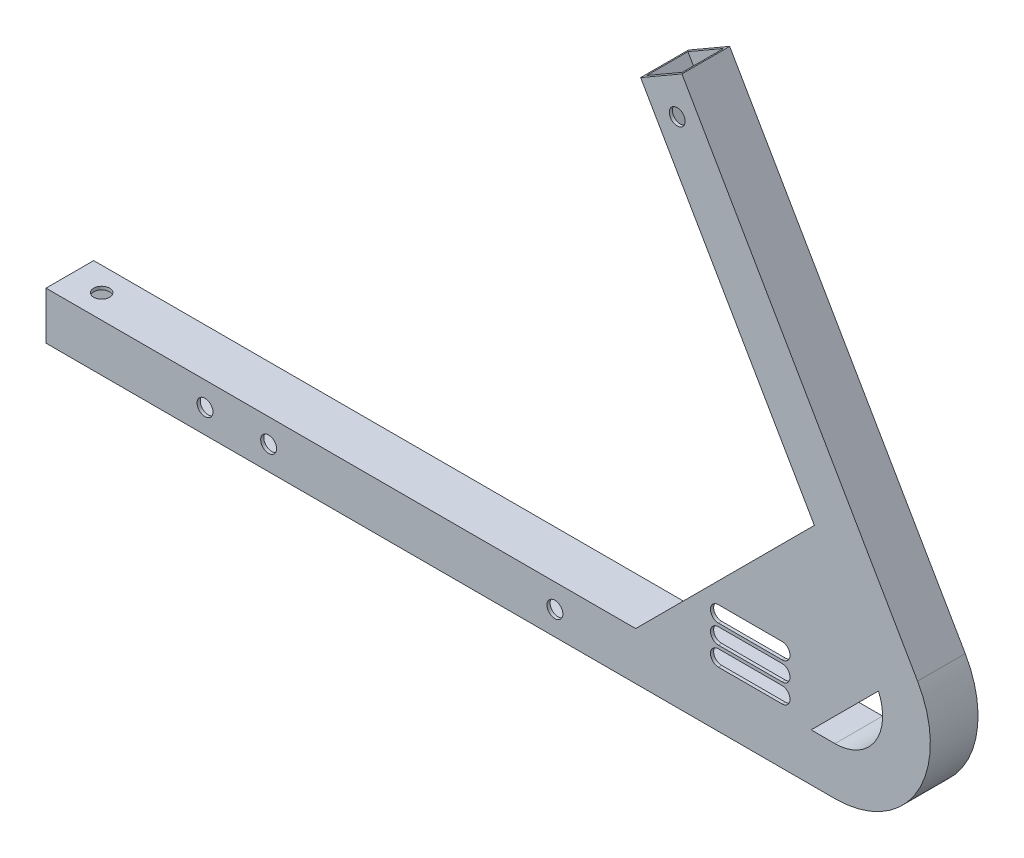
SolidWorks part; units mm, degrees
material "Plain Carbon Steel"
ref_plane "Front Plane" through (0, 0, 0) normal (0, 0, 1) x (1, 0, 0)
ref_plane "Top Plane" through (0, 0, 0) normal (0, 1, 0) x (1, 0, 0)
ref_plane "Right Plane" through (0, 0, 0) normal (1, 0, 0) x (0, 0, -1)
sketch "Sketch1" plane through (0, 0, 0) normal (0, 0, 1) x (1, 0, 0)
  line L0 (102.6529, 330.2) -> (227.3028, 114.3)
  line L1 (161.3117, 0) -> (-468.7061, 0)
  line L2 (69.6573, 311.15) -> (194.3072, 95.25)
  line L3 (161.3117, 38.1) -> (-468.7061, 38.1)
  line L4 (69.6573, 311.15) -> (102.6529, 330.2)
  line L5 (-468.7061, 38.1) -> (-468.7061, 0)
  arc A0 (227.3028, 114.3) -> (161.3117, 0) centre (161.3117, 76.2) cw
  arc A1 (194.3072, 95.25) -> (161.3117, 38.1) centre (161.3117, 76.2) cw
  point P6 (293.2939, 0)
  dimension "D5" = 76.2
  dimension "D1" = 762
  dimension "D2" = 330.2
  dimension "D3" = 60
  dimension "D4" = 254
  dimension "D6" = 38.1
extrude "Boss-Extrude1" add sketch "Sketch1" against normal blind 38.1
shell "Shell1" thickness 2.54
sketch "Sketch3" plane through (-468.7061, 0, 0) normal (-1, 0, 0) x (0, 0, 1)
  line L0 (0, 38.1) -> (0, 0) construction
  line L1 (-35.56, 2.54) -> (-2.54, 2.54)
  line L2 (-35.56, 2.54) -> (-35.56, 35.56)
  line L3 (-35.56, 35.56) -> (-2.54, 35.56)
  line L4 (-2.54, 2.54) -> (-2.54, 35.56)
  line L5 (-35.56, 2.54) -> (-2.54, 35.56) construction
  line L6 (-35.56, 35.56) -> (-2.54, 2.54) construction
  line L7 (-38.1, 38.1) -> (-38.1, 0) construction
  line L8 (-38.1, 0) -> (0, 0) construction
  line L9 (-38.1, 38.1) -> (0, 38.1) construction
  point P0 (-19.05, 19.05)
  dimension "D1" = 2.54
  dimension "D2" = 2.54
  dimension "D3" = 2.54
  dimension "D4" = 2.54
extrude "Cut-Extrude1" cut sketch "Sketch3" against normal up to next
sketch "Sketch4" plane through (0, 0, 0) normal (0, 0, 1) x (1, 0, 0)
  line L0 (2.179, 38.1) -> (144.9018, 180.8228)
  line L1 (161.3117, 38.1) -> (-468.7061, 38.1) construction
  line L2 (69.6573, 311.15) -> (194.3072, 95.25) construction
  line L3 (144.9018, 180.8228) -> (196.1943, 91.9815)
  line L7 (2.179, 38.1) -> (142.3127, 38.1)
  line L8 (142.3127, 38.1) -> (196.1943, 91.9815)
  dimension "D1" = 25.4
  dimension "D2" = 45
  dimension "D3" = 76.2
extrude "Boss-Extrude2" add sketch "Sketch4" against normal blind 2.54
sketch "Sketch5" plane through (0, 0, 0) normal (0, 0, 1) x (1, 0, 0)
  line L1 (-468.7061, 38.1) -> (-468.7061, 0) construction
  line L2 (-468.7061, 0) -> (161.3117, 0) construction
  circle A0 centre (-62.3061, 19.05) radius 6.35
  circle A1 centre (-290.9061, 19.05) radius 6.35
  circle A2 centre (-341.7061, 19.05) radius 6.35
  dimension "D1" = 12.7
  dimension "D2" = 12.7
  dimension "D3" = 12.7
  dimension "D4" = 127
  dimension "D5" = 228.6
  dimension "D6" = 50.8
  dimension "D7" = 19.05
extrude "Cut-Extrude2" cut sketch "Sketch5" against normal through all
sketch "Sketch7" plane through (-117.3176, 203.2, 0) normal (-0.5, 0.866, 0) x (0.866, 0.5, 0)
  line L4 (215.9, 0) -> (254, 0)
  line L5 (254, 0) -> (254, 38.1)
  line L6 (254, 38.1) -> (215.9, 38.1)
  line L7 (215.9, 38.1) -> (215.9, 0)
  line L8 (215.9, 0) -> (254, 0)
  line L9 (254, 0) -> (254, 38.1)
  line L10 (254, 38.1) -> (215.9, 38.1)
  line L11 (215.9, 38.1) -> (215.9, 0)
  line L12 (251.46, 2.54) -> (251.46, 35.56)
  line L13 (218.44, 2.54) -> (251.46, 2.54)
  line L14 (218.44, 35.56) -> (218.44, 2.54)
  line L15 (251.46, 35.56) -> (218.44, 35.56)
  line L16 (251.46, 2.54) -> (251.46, 35.56)
  line L17 (218.44, 2.54) -> (251.46, 2.54)
  line L18 (218.44, 35.56) -> (218.44, 2.54)
  line L19 (251.46, 35.56) -> (218.44, 35.56)
  dimension "D1" = 0
  dimension "D2" = 0
extrude "Boss-Extrude3" add sketch "Sketch7" along normal blind 127
sketch "Sketch8" plane through (0, 38.1, 0) normal (0, 1, 0) x (1, 0, 0)
  line L0 (-468.7061, 38.1) -> (-468.7061, 0) construction
  line L2 (2.179, 2.54) -> (142.3127, 2.54) construction
  circle A0 centre (-443.3061, 19.05) radius 6.35
  dimension "D1" = 12.7
  dimension "D2" = 25.4
  dimension "D3" = 16.51
extrude "Cut-Extrude4" cut sketch "Sketch8" against normal up to next
sketch "Sketch10" plane through (0, 0, -2.54) normal (0, 0, -1) x (-1, 0, 0)
  line L0 (-161.3117, 38.1) -> (468.7061, 38.1) construction
  line L1 (-68.2917, 57.15) -> (-119.0917, 57.15)
  line L2 (-68.2917, 44.45) -> (-119.0917, 44.45)
  line L3 (-68.2917, 72.39) -> (-119.0917, 72.39)
  line L4 (-68.2917, 59.69) -> (-119.0917, 59.69)
  line L5 (-142.3127, 38.1) -> (-196.0533, 91.8406) construction
  line L6 (-68.2917, 87.63) -> (-119.0917, 87.63)
  line L7 (-68.2917, 74.93) -> (-119.0917, 74.93)
  arc A0 (-68.2917, 44.45) -> (-68.2917, 57.15) centre (-68.2917, 50.8) ccw
  arc A1 (-119.0917, 57.15) -> (-119.0917, 44.45) centre (-119.0917, 50.8) ccw
  arc A2 (-68.2917, 59.69) -> (-68.2917, 72.39) centre (-68.2917, 66.04) ccw
  arc A3 (-119.0917, 72.39) -> (-119.0917, 59.69) centre (-119.0917, 66.04) ccw
  arc A4 (-68.2917, 74.93) -> (-68.2917, 87.63) centre (-68.2917, 81.28) ccw
  arc A5 (-119.0917, 87.63) -> (-119.0917, 74.93) centre (-119.0917, 81.28) ccw
  dimension "D1" = 12.7
  dimension "D2" = 12.7
  dimension "D5" = 3
  dimension "D4" = 25.4
  dimension "D3" = 50.8
  dimension "D6" = 27.94
extrude "Cut-Extrude6" cut sketch "Sketch10" against normal through all both and the other way through all
sketch "Sketch11" plane through (0, 0, 0) normal (0, 0, 1) x (1, 0, 0)
  line L0 (22.6551, 430.6602) -> (131.576, 242.0037) construction
  line L1 (6.1573, 421.1352) -> (39.1529, 440.1852) construction
  line L2 (68.2917, 87.63) -> (119.0917, 87.63) construction
  circle A0 centre (35.3665, 408.6434) radius 6.35
  dimension "D1" = 12.7
  dimension "D2" = 83.7252
  dimension "D3" = 321.0134
extrude "Cut-Extrude7" cut sketch "Sketch11" against normal up to next
